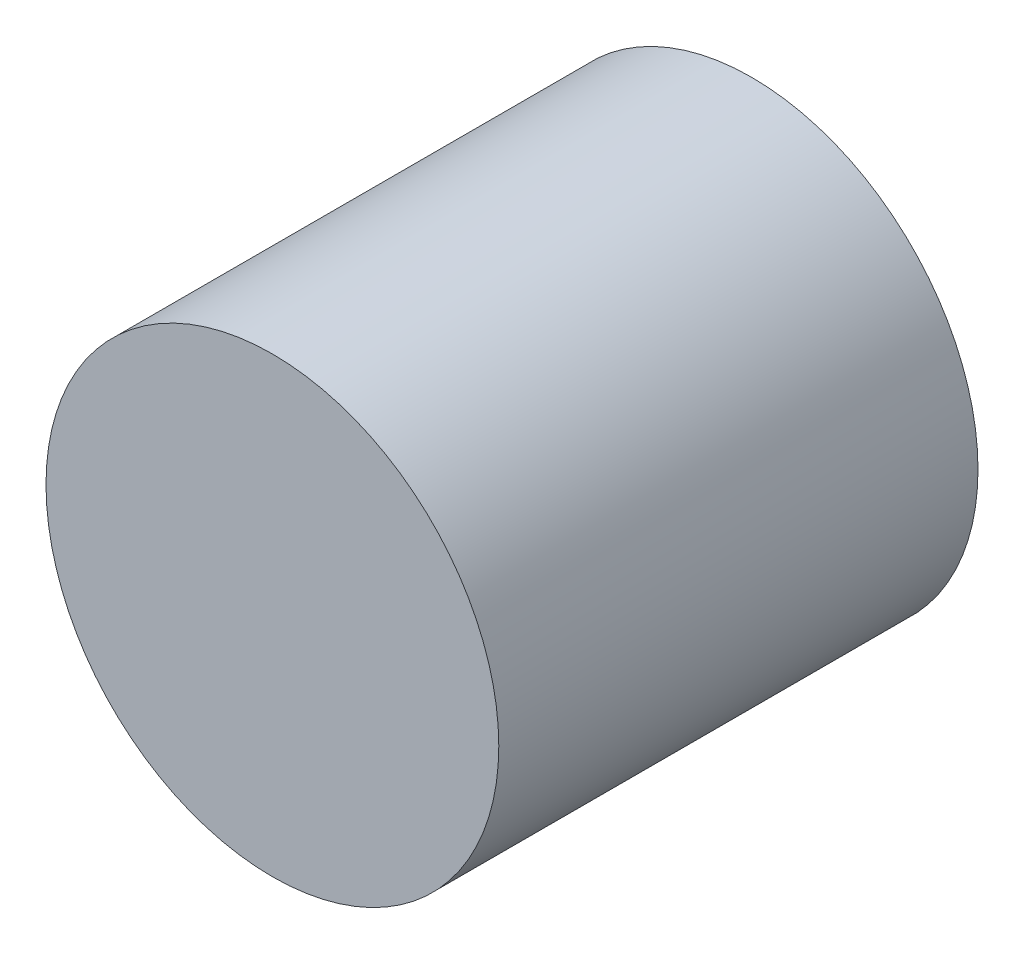
SolidWorks part; units mm, degrees
ref_plane "Front Plane" through (0, 0, 0) normal (0, 0, 1) x (1, 0, 0)
ref_plane "Top Plane" through (0, 0, 0) normal (0, 1, 0) x (1, 0, 0)
ref_plane "Right Plane" through (0, 0, 0) normal (1, 0, 0) x (0, 0, -1)
sketch "Sketch1" plane through (0, 0, 0) normal (0, 0, 1) x (1, 0, 0)
  circle A0 centre (0, 0) radius 3
  dimension "D1" = 6
extrude "Boss-Extrude1" add sketch "Sketch1" along normal blind 6.35
